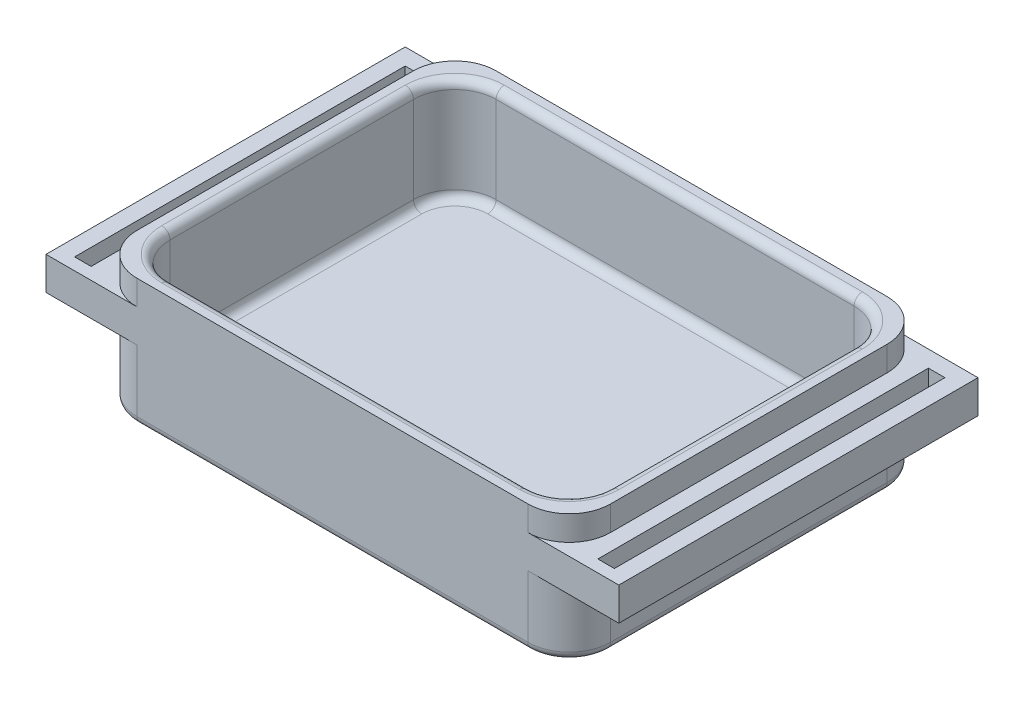
SolidWorks part; units mm, degrees
ref_plane "Front Plane" through (0, 0, 0) normal (0, 0, 1) x (1, 0, 0)
ref_plane "Top Plane" through (0, 0, 0) normal (0, 1, 0) x (1, 0, 0)
ref_plane "Right Plane" through (0, 0, 0) normal (1, 0, 0) x (0, 0, -1)
sketch "Sketch1" plane through (0, 0, 0) normal (0, 1, 0) x (1, 0, 0)
  line L1 (-20.155, 15.23) -> (20.155, 15.23)
  line L2 (-20.155, 15.23) -> (-20.155, -15.23)
  line L3 (-20.155, -15.23) -> (20.155, -15.23)
  line L4 (20.155, 15.23) -> (20.155, -15.23)
  line L5 (-26.155, 4.24) -> (-20.155, 4.24)
  line L6 (-26.155, 4.24) -> (-26.155, -11.5)
  line L7 (-26.155, -11.5) -> (-20.155, -11.5)
  line L8 (-20.155, 4.24) -> (-20.155, -11.5)
  circle A0 centre (17.845, 12.5) radius 1
  circle A1 centre (17.845, -11.5) radius 1
  circle A2 centre (-18.155, -11.5) radius 1
  dimension "D5" = 2
  dimension "D8" = 3.73
  dimension "D10" = 2
  dimension "D11" = 3.73
  dimension "D13" = 2
  dimension "D1" = 40.31
  dimension "D2" = 30.46
  dimension "D3" = 15.23
  dimension "D4" = 20.155
  dimension "D6" = 2.73
  dimension "D7" = 2.31
  dimension "D9" = 2.31
  dimension "D12" = 2
  dimension "D14" = 15.74
  dimension "D15" = 6
  dimension "D16" = 8
  dimension "D17" = 0
sketch "Sketch2" plane through (0, 0, 0) normal (0, 1, 0) x (1, 0, 0)
  line L0 (-20.155, 15.23) -> (20.155, 15.23) construction
  line L1 (-29.655, 18.23) -> (23.655, 18.23)
  line L2 (-29.655, 18.23) -> (-29.655, -21.23)
  line L3 (-29.655, -21.23) -> (23.655, -21.23)
  line L4 (23.655, 18.23) -> (23.655, -21.23)
  line L5 (-20.155, -15.23) -> (20.155, -15.23) construction
  line L6 (20.155, 15.23) -> (20.155, -15.23) construction
  line L7 (-26.155, 4.24) -> (-26.155, -11.5) construction
  line L9 (-31.655, 20.23) -> (25.655, 20.23)
  line L10 (-31.655, 20.23) -> (-31.655, -23.23)
  line L11 (-31.655, -23.23) -> (25.655, -23.23)
  line L12 (25.655, 20.23) -> (25.655, -23.23)
  dimension "D1" = 3
  dimension "D2" = 6
  dimension "D3" = 3.5
  dimension "D4" = 3.5
  dimension "D5" = 2
  dimension "D6" = 2
  dimension "D7" = 2
  dimension "D8" = 2
extrude "Boss-Extrude1" add sketch "Sketch2" along normal blind 5 and the other way blind 7.5
fillet "Fillet1" radius 5 8 edges at (-31.655, -1.25, -20.23) (25.655, -1.25, -20.23) (25.655, -1.25, 23.23) (-31.655, -1.25, 23.23) (23.655, -1.25, 21.23) (-29.655, -1.25, 21.23) (23.655, -1.25, -18.23) (-29.655, -1.25, -18.23)
sketch "Sketch3" plane through (0, -7.5, 0) normal (0, -1, 0) x (1, 0, 0)
  line L4 (-31.655, 18.23) -> (-31.655, -15.23)
  line L5 (-26.655, -20.23) -> (20.655, -20.23)
  line L6 (25.655, -15.23) -> (25.655, 18.23)
  line L7 (20.655, 23.23) -> (-26.655, 23.23)
  line L8 (-31.655, 18.23) -> (-31.655, -15.23)
  line L9 (-26.655, -20.23) -> (20.655, -20.23)
  line L10 (25.655, -15.23) -> (25.655, 18.23)
  line L11 (20.655, 23.23) -> (-26.655, 23.23)
  circle A0 centre (-18.155, 11.5) radius 1
  circle A1 centre (17.845, 11.5) radius 1
  circle A2 centre (17.845, -12.5) radius 1
  arc A4 (-31.655, -15.23) -> (-26.655, -20.23) centre (-26.655, -15.23) ccw
  arc A5 (20.655, -20.23) -> (25.655, -15.23) centre (20.655, -15.23) ccw
  arc A6 (25.655, 18.23) -> (20.655, 23.23) centre (20.655, 18.23) ccw
  arc A7 (-26.655, 23.23) -> (-31.655, 18.23) centre (-26.655, 18.23) ccw
  arc A8 (-31.655, -15.23) -> (-26.655, -20.23) centre (-26.655, -15.23) ccw
  arc A9 (20.655, -20.23) -> (25.655, -15.23) centre (20.655, -15.23) ccw
  arc A10 (25.655, 18.23) -> (20.655, 23.23) centre (20.655, 18.23) ccw
  arc A11 (-26.655, 23.23) -> (-31.655, 18.23) centre (-26.655, 18.23) ccw
  dimension "D1" = 0
extrude "Boss-Extrude2" add sketch "Sketch3" along normal blind 3
sketch "Sketch5" plane through (0, -10.5, 0) normal (0, -1, 0) x (1, 0, 0)
  line L0 (-18.155, 13.9249) -> (-20.255, 12.7124)
  line L1 (-16.055, 12.7124) -> (-18.155, 13.9249)
  line L2 (-20.255, 12.7124) -> (-20.255, 10.2876)
  line L3 (-16.055, 10.2876) -> (-16.055, 12.7124)
  line L5 (-18.155, 9.0751) -> (-16.055, 10.2876)
  line L6 (-20.255, 10.2876) -> (-18.155, 9.0751)
  line L7 (17.8578, 13.9054) -> (15.745, 12.6856)
  line L8 (19.945, 12.7004) -> (17.8578, 13.9054)
  line L9 (15.745, 12.6856) -> (15.745, 10.2755)
  line L10 (19.945, 10.2607) -> (19.945, 12.7004)
  line L12 (17.8578, 9.0556) -> (19.945, 10.2607)
  line L13 (15.745, 10.2755) -> (17.8578, 9.0556)
  line L14 (17.8338, -10.0869) -> (15.7338, -11.2994)
  line L15 (19.9338, -11.2994) -> (17.8338, -10.0869)
  line L16 (15.7338, -11.2994) -> (15.7338, -13.7242)
  line L17 (19.9338, -13.7242) -> (19.9338, -11.2994)
  line L19 (17.8338, -14.9367) -> (19.9338, -13.7242)
  line L20 (15.7338, -13.7242) -> (17.8338, -14.9367)
  circle A0 centre (-18.155, 11.5) radius 1 construction
  circle A1 centre (17.845, 11.5) radius 1
  circle A2 centre (17.845, -12.5) radius 1
  circle A3 centre (-18.155, 11.5) radius 2.1 construction
  circle A4 centre (17.845, 11.5) radius 1 construction
  circle A5 centre (17.845, 11.5) radius 2.1 construction
  circle A6 centre (17.8338, -12.5118) radius 1 construction
  circle A7 centre (17.8338, -12.5118) radius 2.1 construction
  point P23 (0, 0)
  point P26 (17.8578, 11.4805)
  point P28 (-18.155, 11.5)
  point P36 (17.8338, -12.5118)
  dimension "D1" = 4.2
  dimension "D4" = 4.2
  dimension "D6" = 4.2
  dimension "D2" = 6
  dimension "D3" = 4.8497
  dimension "D5" = 4.8497
  dimension "D7" = 4.8497
extrude "Cut-Extrude1" cut sketch "Sketch5" against normal blind 2 draft 3 draft outward yes
fillet "Fillet2" radius 1 16 edges at (-28.1905, -7.5, -16.7655) (-3, -7.5, -18.23) (22.1905, -7.5, -16.7655) (23.655, -7.5, 1.5) (22.1905, -7.5, 19.7655) (-3, -7.5, 21.23) (-28.1905, -7.5, 19.7655) (-29.655, -7.5, 1.5) (-28.1905, 5, -16.7655) (-3, 5, -18.23) (22.1905, 5, -16.7655) (23.655, 5, 1.5) (22.1905, 5, 19.7655) (-3, 5, 21.23) (-28.1905, 5, 19.7655) (-29.655, 5, 1.5)
sketch "Sketch6" plane through (0, 0, 0) normal (0, 1, 0) x (1, 0, 0)
  line L0 (-37.655, 20.23) -> (-37.655, -23.23)
  line L1 (20.655, 20.23) -> (31.655, 20.23)
  line L2 (25.655, 15.23) -> (25.655, -18.23)
  line L3 (-31.655, 15.23) -> (-31.655, -18.23) construction
  line L4 (31.655, 20.23) -> (31.655, -23.23)
  line L5 (-31.655, 15.23) -> (-31.655, -18.23)
  line L6 (20.655, -23.23) -> (31.655, -23.23)
  line L7 (27.655, 18.23) -> (29.655, 18.23)
  line L8 (27.655, 18.23) -> (27.655, -21.77)
  line L9 (27.655, -21.77) -> (29.655, -21.77)
  line L10 (29.655, 18.23) -> (29.655, -21.77)
  line L11 (-26.655, 20.23) -> (-37.655, 20.23)
  line L12 (-37.655, -23.23) -> (-26.655, -23.23)
  line L14 (-35.655, 18.23) -> (-33.655, 18.23)
  line L15 (-35.655, 18.23) -> (-35.655, -21.77)
  line L16 (-35.655, -21.77) -> (-33.655, -21.77)
  line L17 (-33.655, 18.23) -> (-33.655, -21.77)
  arc A0 (25.655, 15.23) -> (20.655, 20.23) centre (20.655, 15.23) ccw construction
  arc A1 (20.655, -23.23) -> (25.655, -18.23) centre (20.655, -18.23) ccw construction
  arc A2 (25.655, 15.23) -> (20.655, 20.23) centre (20.655, 15.23) ccw
  arc A3 (20.655, -23.23) -> (25.655, -18.23) centre (20.655, -18.23) ccw
  arc A4 (-26.655, 20.23) -> (-31.655, 15.23) centre (-26.655, 15.23) ccw construction
  arc A5 (-31.655, -18.23) -> (-26.655, -23.23) centre (-26.655, -18.23) ccw construction
  arc A7 (-26.655, 20.23) -> (-31.655, 15.23) centre (-26.655, 15.23) ccw
  arc A8 (-31.655, -18.23) -> (-26.655, -23.23) centre (-26.655, -18.23) ccw
  dimension "D1" = 6
  dimension "D2" = 2
  dimension "D3" = 2
  dimension "D4" = 40
  dimension "D5" = 2
  dimension "D6" = 6
  dimension "D7" = 2
  dimension "D8" = 2
  dimension "D9" = 40
  dimension "D10" = 2
extrude "Boss-Extrude3" add sketch "Sketch6" against normal mid plane 4
fillet "Fillet3" radius 1 8 edges at (24.1905, -10.5, -18.7655) (-3, -10.5, -20.23) (-30.1905, -10.5, -18.7655) (-31.655, -10.5, 1.5) (-30.1905, -10.5, 21.7655) (-3, -10.5, 23.23) (24.1905, -10.5, 21.7655) (25.655, -10.5, 1.5)
